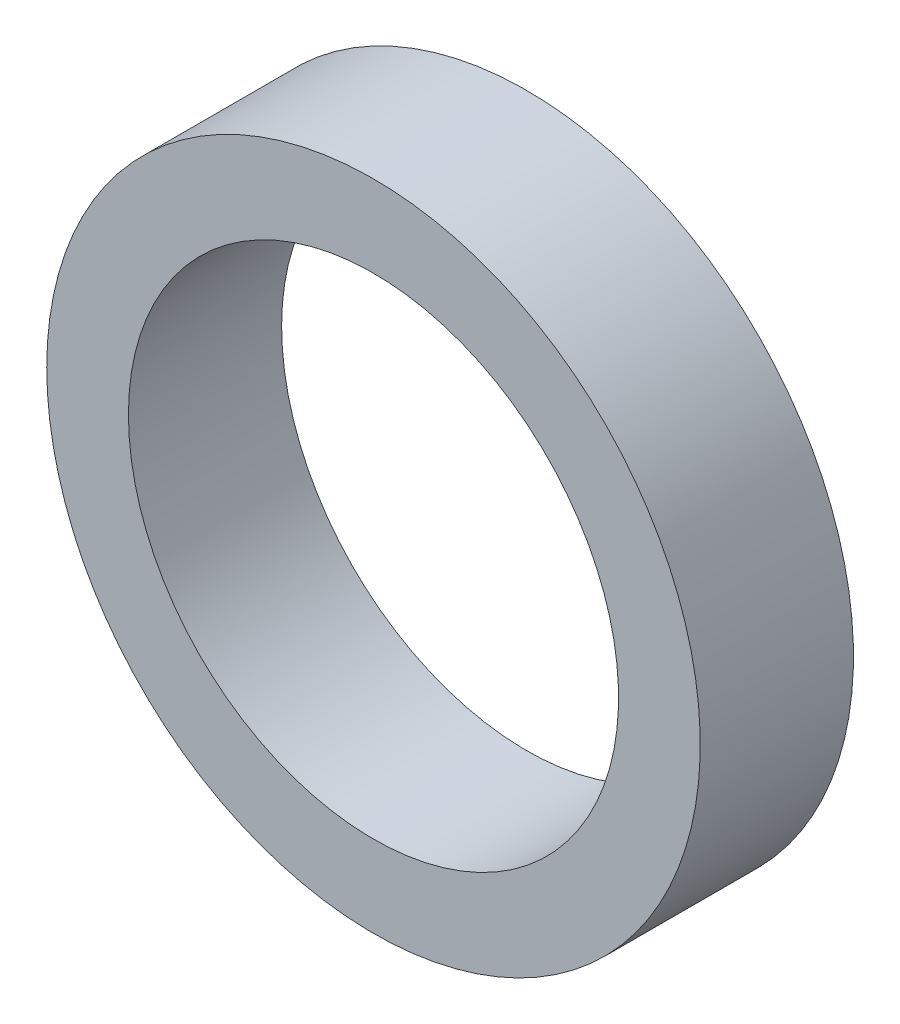
SolidWorks part; units mm, degrees
ref_plane "Front Plane" through (0, 0, 0) normal (0, 0, 1) x (1, 0, 0)
ref_plane "Top Plane" through (0, 0, 0) normal (0, 1, 0) x (1, 0, 0)
ref_plane "Right Plane" through (0, 0, 0) normal (1, 0, 0) x (0, 0, -1)
sketch "Sketch1" plane through (0, 0, 0) normal (0, 0, 1) x (1, 0, 0)
  circle A0 centre (0, 0) radius 7.62
  circle A1 centre (0, 0) radius 10.16
  dimension "D1" = 15.24
  dimension "D2" = 2.54
extrude "Boss-Extrude1" add sketch "Sketch1" along normal blind 4.7625
